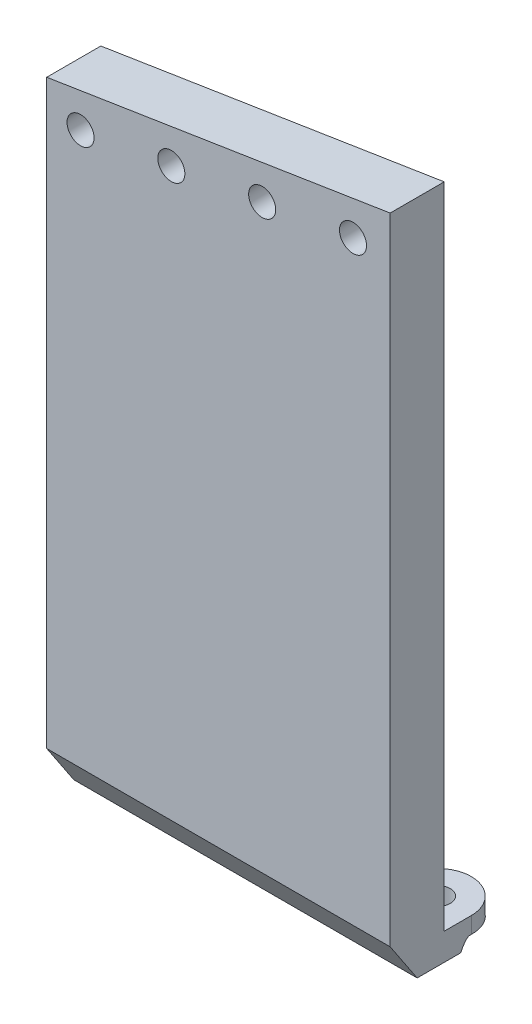
SolidWorks part; units mm, degrees
ref_plane "Front Plane" through (0, 0, 0) normal (0, 0, 1) x (1, 0, 0)
ref_plane "Top Plane" through (0, 0, 0) normal (0, 1, 0) x (1, 0, 0)
ref_plane "Right Plane" through (0, 0, 0) normal (1, 0, 0) x (0, 0, -1)
sketch "Sketch1" plane through (0, 0, 0) normal (0, 1, 0) x (1, 0, 0)
  line L1 (0, 0) -> (32.258, 0)
  line L2 (0, 0) -> (0, 7.62)
  line L3 (6.35, 7.62) -> (25.908, 7.62)
  line L4 (32.258, 0) -> (32.258, 7.62)
  arc A0 (0, 7.62) -> (6.35, 7.62) centre (3.175, 7.62) cw
  arc A1 (32.258, 7.62) -> (25.908, 7.62) centre (29.083, 7.62) ccw
  circle A2 centre (3.175, 7.62) radius 1.2065
  circle A3 centre (29.083, 7.62) radius 1.2065
  dimension "D7" = 2.413
  dimension "D8" = 2.413
  dimension "D1" = 6.35
  dimension "D2" = 6.35
  dimension "D3" = 32.258
  dimension "D4" = 7.62
  dimension "D5" = 7.62
  dimension "D6" = 7.62
extrude "Boss-Extrude1" add sketch "Sketch1" along normal blind 2.54
sketch "Sketch2" plane through (0, 2.54, 0) normal (0, 1, 0) x (1, 0, 0)
  line L0 (32.258, 0) -> (32.258, 7.62) construction
  line L1 (0, 0) -> (32.258, 0)
  line L2 (0, 0) -> (0, 5.08)
  line L3 (0, 5.08) -> (32.258, 5.08)
  line L4 (32.258, 0) -> (32.258, 5.08)
  dimension "D1" = 5.08
extrude "Boss-Extrude2" add sketch "Sketch2" along normal blind 60.96
sketch "Sketch4" plane through (0, 0, 0) normal (0, 0, 1) x (1, 0, 0)
  line L0 (32.258, 63.5) -> (0, 58.42)
  line L1 (0, 63.5) -> (0, 0) construction
  line L2 (0, 58.42) -> (0, 63.5)
  line L3 (0, 63.5) -> (32.258, 63.5)
  dimension "D1" = 5.08
extrude "Cut-Extrude2" cut sketch "Sketch4" against normal up to surface (5.08 mm away) up to face at (20.1613, 48.26, -5.08)
sketch "Sketch3" plane through (0, 0, -5.08) normal (0, 0, -1) x (-1, 0, 0)
  line L2 (0, 58.42) -> (0, 2.54) construction
  line L3 (-32.258, 63.5) -> (0, 58.42) construction
  line L4 (-3.175, 55.7059) -> (-28.7676, 59.7362)
  circle A0 centre (-28.7676, 59.7362) radius 1.27
  circle A1 centre (-20.2367, 58.3928) radius 1.27
  circle A2 centre (-11.7059, 57.0493) radius 1.27
  circle A3 centre (-3.175, 55.7059) radius 1.27
  dimension "D1" = 2.54
  dimension "D2" = 3.175
  dimension "D3" = 25.908
  dimension "D4" = 3.175
  dimension "D5" = 8.636
  dimension "D6" = 8.636
  dimension "D7" = 3.175
  dimension "D8" = 3.175
  dimension "D9" = 3.175
extrude "Cut-Extrude1" cut sketch "Sketch3" against normal up to surface (5.08 mm away) up to face at (16.129, 30.48, 0)
sketch "Sketch5" plane through (0, 0, 0) normal (-1, 0, 0) x (0, 0, 1)
  line L0 (0, 0) -> (-2.54, 0)
  line L1 (-7.62, 0) -> (0, 0) construction
  line L2 (-2.54, 0) -> (0, 3.81)
  line L3 (0, 58.42) -> (0, 0) construction
  line L4 (0, 3.81) -> (0, 0)
  dimension "D1" = 3.81
  dimension "D2" = 2.54
extrude "Cut-Extrude3" cut sketch "Sketch5" against normal up to surface (32.258 mm away) up to face at (32.258, 27.0933, -4.0217)
ref_plane "Plane1" through (0.627, -3.9813, 0) normal (-0.1556, 0.9878, 0) x (0.9878, 0.1556, 0)
sketch "Sketch6" plane through (0.627, -3.9813, 0) normal (-0.1556, 0.9878, 0) x (0.9878, 0.1556, 0)
  circle A0 centre (28.8119, 7.6479) radius 3.2194
extrude "Cut-Extrude4" cut sketch "Sketch6" against normal blind 2.54
ref_plane "Plane2" through (0, 0, 0) normal (-0.1556, 0.9878, 0) x (0.9878, 0.1556, 0)
sketch "Sketch7" plane through (0, 0, 0) normal (-0.1556, 0.9878, 0) x (0.9878, 0.1556, 0)
  circle A0 centre (3.216, 7.6159) radius 3.216
extrude "Cut-Extrude5" cut sketch "Sketch7" against normal blind 2.54
mirror "Mirror1" about plane through (32.258, 2.54, 0) normal (-1, 0, 0) of bodies 107
sketch "Sketch8" plane through (0, 0, -5.08) normal (0, 0, -1) x (-1, 0, 0)
  line L1 (-32.258, 63.5) -> (2.3799, 63.5)
  line L2 (-32.258, 63.5) -> (-32.258, -5.4947)
  line L3 (-32.258, -5.4947) -> (2.3799, -5.4947)
  line L4 (2.3799, 63.5) -> (2.3799, -5.4947)
extrude "Cut-Extrude7" cut sketch "Sketch8" against normal through all and the other way through all
mirror "Mirror2" about plane through (32.258, 63.5, 0) normal (1, 0, 0) of bodies 110
sketch "Sketch9" plane through (0, 0, -5.08) normal (0, 0, -1) x (-1, 0, 0)
  line L1 (-32.258, 63.5) -> (-71.1664, 63.5)
  line L2 (-32.258, 63.5) -> (-32.258, -7.5192)
  line L3 (-32.258, -7.5192) -> (-71.1664, -7.5192)
  line L4 (-71.1664, 63.5) -> (-71.1664, -7.5192)
extrude "Cut-Extrude9" cut sketch "Sketch9" against normal through all and the other way through all
